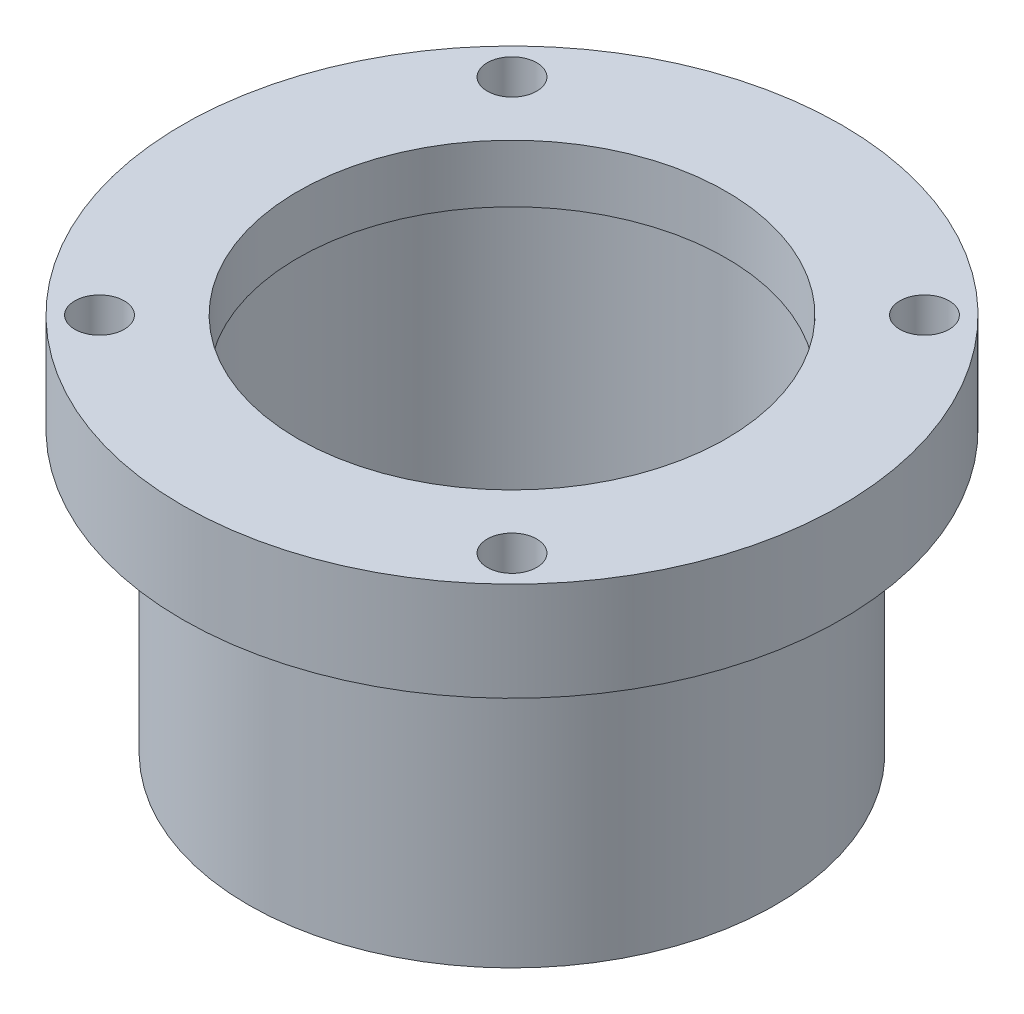
SolidWorks part; units mm, degrees
other "Bearing Cartridge"
ref_plane "Front Plane" through (0, 0, 0) normal (0, 0, 1) x (1, 0, 0)
ref_plane "Top Plane" through (0, 0, 0) normal (0, 1, 0) x (1, 0, 0)
ref_plane "Right Plane" through (0, 0, 0) normal (1, 0, 0) x (0, 0, -1)
sketch3d "Cartridge barrel sketch datum points"
  point P0 (-19.0092, -237.5, -53.2449)
  point P1 (-9.0092, -237.5, -53.2449)
  point P2 (-19.0092, -237.5, -63.2449)
ref_plane "Cartridge barrel sketch plane" through (0, -237.5, 0) normal (0, 1, 0) x (1, 0, 0)
sketch "Cartridge barrel sketch" plane through (0, -237.5, 0) normal (0, 1, 0) x (1, 0, 0)
  circle A0 centre (-19.0092, 53.2449) radius 16
extrude "Cartridge barrel" add sketch "Cartridge barrel sketch" along normal blind 17 separate body
sketch3d "Six millimetre flange sketch datum points"
  point P0 (-19.0092, -220.5, -53.2449)
  point P1 (-9.0092, -220.5, -53.2449)
  point P2 (-19.0092, -220.5, -63.2449)
ref_plane "Six millimetre flange sketch plane" through (0, -220.5, 0) normal (0, 1, 0) x (1, 0, 0)
sketch "Six millimetre flange sketch" plane through (0, -220.5, 0) normal (0, 1, 0) x (1, 0, 0)
  circle A0 centre (-19.0092, 53.2449) radius 20
extrude "Six millimetre flange" add sketch "Six millimetre flange sketch" along normal blind 6
sketch3d "Bearing bore sketch datum points"
  point P0 (-19.0092, -237.6, -53.2449)
  point P1 (-9.0092, -237.6, -53.2449)
  point P2 (-19.0092, -237.6, -63.2449)
ref_plane "Bearing bore sketch plane" through (0, -237.6, 0) normal (0, 1, 0) x (1, 0, 0)
sketch "Bearing bore sketch" plane through (0, -237.6, 0) normal (0, 1, 0) x (1, 0, 0)
  circle A0 centre (-19.0092, 53.2449) radius 14
extrude "Bearing bore" cut sketch "Bearing bore sketch" along normal blind 19.6
sketch3d "Outer race shoulder exit sketch datum points"
  point P0 (-19.0092, -218, -53.2449)
  point P1 (-9.0092, -218, -53.2449)
  point P2 (-19.0092, -218, -63.2449)
ref_plane "Outer race shoulder exit sketch plane" through (0, -218, 0) normal (0, 1, 0) x (1, 0, 0)
sketch "Outer race shoulder exit sketch" plane through (0, -218, 0) normal (0, 1, 0) x (1, 0, 0)
  circle A0 centre (-19.0092, 53.2449) radius 13
extrude "Outer race shoulder exit" cut sketch "Outer race shoulder exit sketch" along normal blind 3.6
sketch3d "M3 tapped hole pattern sketch datum points"
  point P0 (-19.0092, -220.6, -53.2449)
  point P1 (-9.0092, -220.6, -53.2449)
  point P2 (-19.0092, -220.6, -63.2449)
ref_plane "M3 tapped hole pattern sketch plane" through (0, -220.6, 0) normal (0, 1, 0) x (1, 0, 0)
sketch "M3 tapped hole pattern sketch" plane through (0, -220.6, 0) normal (0, 1, 0) x (1, 0, 0)
  circle A0 centre (-6.4934, 40.7291) radius 1.5
  circle A1 centre (-31.525, 40.7291) radius 1.5
  circle A2 centre (-31.525, 65.7607) radius 1.5
  circle A3 centre (-6.4934, 65.7607) radius 1.5
extrude "M3 tapped hole pattern" cut sketch "M3 tapped hole pattern sketch" along normal blind 6.2
